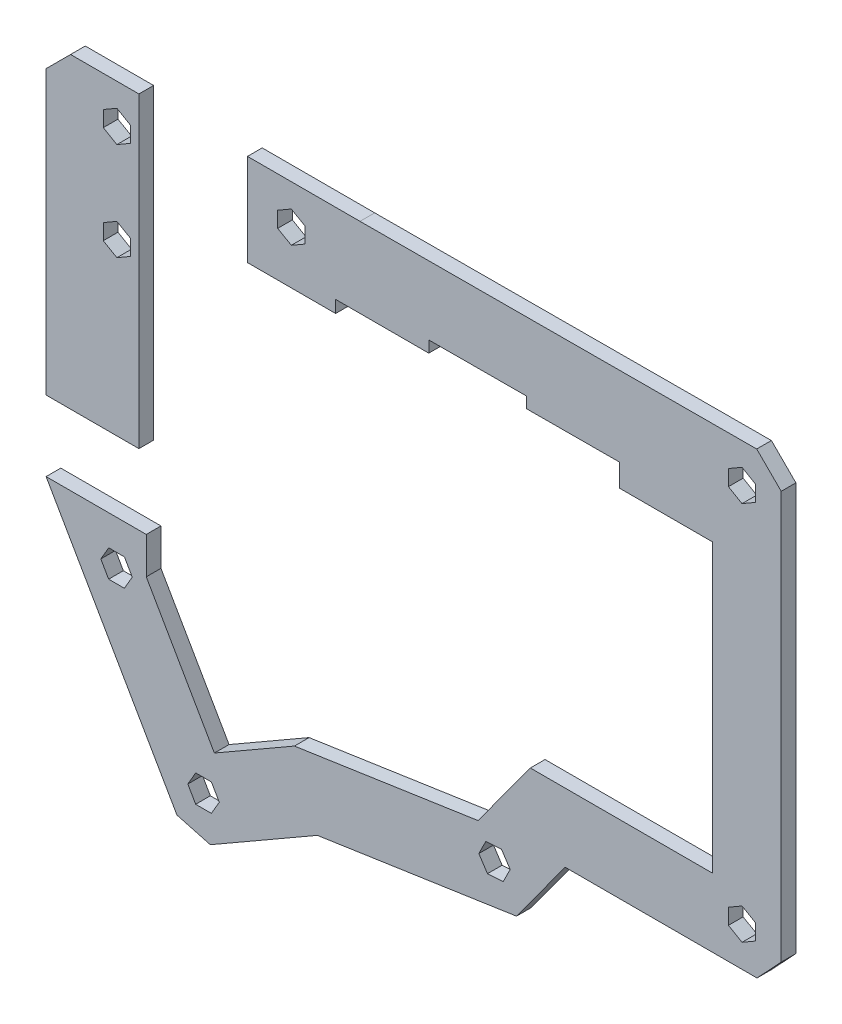
SolidWorks part; units mm, degrees
ref_plane "Plan de face" through (0, 0, 0) normal (0, 0, 1) x (1, 0, 0)
ref_plane "Plan de dessus" through (0, 0, 0) normal (0, 1, 0) x (1, 0, 0)
ref_plane "Plan de droite" through (0, 0, 0) normal (1, 0, 0) x (0, 0, -1)
sketch "Esquisse1" plane through (0, 0, 0) normal (0, 0, 1) x (1, 0, 0)
  line L0 (-117.3419, -15.4198) -> (-103.3409, -15.4198) construction
  line L1 (-103.3409, -15.4198) -> (-103.3409, -29.4208) construction
  line L2 (-103.3409, -29.4208) -> (-117.3419, -29.4208) construction
  line L3 (-117.3419, -29.4208) -> (-117.3419, -15.4198) construction
  line L4 (-98.3406, -27.0457) -> (-98.3406, -13.0447) construction
  line L5 (-98.3406, -13.0447) -> (-84.3396, -13.0447) construction
  line L6 (-84.3396, -13.0447) -> (-84.3396, -27.0457) construction
  line L7 (-84.3396, -27.0457) -> (-98.3406, -27.0457) construction
  line L8 (-79.3392, -24.6705) -> (-79.3392, -10.6695) construction
  line L9 (-79.3392, -10.6695) -> (-65.3382, -10.6695) construction
  line L10 (-65.3382, -10.6695) -> (-65.3382, -24.6705) construction
  line L11 (-65.3382, -24.6705) -> (-79.3392, -24.6705) construction
  line L12 (-60.3379, -27.0457) -> (-60.3379, -13.0447) construction
  line L13 (-60.3379, -13.0447) -> (-46.3369, -13.0447) construction
  line L14 (-46.3369, -13.0447) -> (-46.3369, -27.0457) construction
  line L15 (-46.3369, -27.0457) -> (-60.3379, -27.0457) construction
  line L16 (-41.3365, -31.796) -> (-41.3365, -17.795) construction
  line L17 (-41.3365, -17.795) -> (-27.3355, -17.795) construction
  line L18 (-27.3355, -17.795) -> (-27.3355, -31.796) construction
  line L19 (-27.3355, -31.796) -> (-41.3365, -31.796) construction
  line L20 (-22.3347, -31.796) -> (-22.3347, -17.795) construction
  line L21 (-22.3347, -17.795) -> (-8.3337, -17.795) construction
  line L22 (-8.3337, -17.795) -> (-8.3337, -31.796)
  line L23 (-8.3337, -31.796) -> (-22.3347, -31.796) construction
  line L24 (-117.3419, -34.4212) -> (-103.3409, -34.4212) construction
  line L25 (-103.3409, -34.4212) -> (-103.3409, -48.4222) construction
  line L26 (-103.3409, -48.4222) -> (-117.3419, -48.4222) construction
  line L27 (-117.3419, -48.4222) -> (-117.3419, -34.4212) construction
  line L28 (-98.3406, -32.046) -> (-84.3396, -32.046) construction
  line L29 (-84.3396, -32.046) -> (-84.3396, -46.047) construction
  line L30 (-84.3396, -46.047) -> (-98.3406, -46.047) construction
  line L31 (-98.3406, -46.047) -> (-98.3406, -32.046) construction
  line L32 (-79.3392, -29.6709) -> (-65.3382, -29.6709) construction
  line L33 (-65.3382, -29.6709) -> (-65.3382, -43.6718) construction
  line L34 (-65.3382, -43.6718) -> (-79.3392, -43.6718) construction
  line L35 (-79.3392, -43.6718) -> (-79.3392, -29.6709) construction
  line L36 (-60.3379, -32.046) -> (-46.3369, -32.046) construction
  line L37 (-46.3369, -32.046) -> (-46.3369, -46.047) construction
  line L38 (-46.3369, -46.047) -> (-60.3379, -46.047) construction
  line L39 (-60.3379, -46.047) -> (-60.3379, -32.046) construction
  line L40 (-41.3365, -36.7964) -> (-27.3355, -36.7964) construction
  line L41 (-27.3355, -36.7964) -> (-27.3355, -50.7973) construction
  line L42 (-27.3355, -50.7973) -> (-41.3365, -50.7973) construction
  line L43 (-41.3365, -50.7973) -> (-41.3365, -36.7964) construction
  line L44 (-22.3347, -36.7964) -> (-8.3337, -36.7964) construction
  line L45 (-8.3337, -36.7964) -> (-8.3337, -50.7973) construction
  line L46 (-8.3337, -50.7973) -> (-22.3347, -50.7973) construction
  line L47 (-22.3347, -50.7973) -> (-22.3347, -36.7964) construction
  line L48 (-22.3347, -55.7977) -> (-8.3337, -55.7977) construction
  line L49 (-8.3337, -55.7977) -> (-8.3337, -69.7987) construction
  line L50 (-8.3337, -69.7987) -> (-22.3347, -69.7987) construction
  line L51 (-22.3347, -69.7987) -> (-22.3347, -55.7977) construction
  line L52 (-41.3365, -55.7977) -> (-27.3355, -55.7977) construction
  line L53 (-27.3355, -55.7977) -> (-27.3355, -69.7987) construction
  line L54 (-27.3355, -69.7987) -> (-41.3365, -69.7987) construction
  line L55 (-41.3365, -69.7987) -> (-41.3365, -55.7977) construction
  line L56 (-60.3379, -51.0474) -> (-46.3369, -51.0474) construction
  line L57 (-46.3369, -51.0474) -> (-46.3369, -65.0484) construction
  line L58 (-46.3369, -65.0484) -> (-60.3379, -65.0484) construction
  line L59 (-60.3379, -65.0484) -> (-60.3379, -51.0474) construction
  line L60 (-79.3392, -48.6722) -> (-65.3382, -48.6722) construction
  line L61 (-65.3382, -48.6722) -> (-65.3382, -62.6732) construction
  line L62 (-65.3382, -62.6732) -> (-79.3392, -62.6732) construction
  line L63 (-79.3392, -62.6732) -> (-79.3392, -48.6722) construction
  line L64 (-98.3406, -51.0474) -> (-84.3396, -51.0474) construction
  line L65 (-84.3396, -51.0474) -> (-84.3396, -65.0484) construction
  line L66 (-84.3396, -65.0484) -> (-98.3406, -65.0484) construction
  line L67 (-98.3406, -65.0484) -> (-98.3406, -51.0474) construction
  line L68 (-117.3419, -53.4225) -> (-103.3409, -53.4225) construction
  line L69 (-103.3409, -53.4225) -> (-103.3409, -67.4235) construction
  line L70 (-103.3409, -67.4235) -> (-117.3419, -67.4235) construction
  line L71 (-117.3419, -67.4235) -> (-117.3419, -53.4225) construction
  line L72 (-88.8399, -70.6738) -> (-74.8389, -70.6738) construction
  line L73 (-74.8389, -70.6738) -> (-74.8389, -84.6747) construction
  line L74 (-74.8389, -84.6747) -> (-88.8399, -84.6747) construction
  line L75 (-88.8399, -84.6747) -> (-88.8399, -70.6738) construction
  line L76 (-111.4175, -75.4665) -> (-97.8899, -71.8565) construction
  line L77 (-97.8899, -71.8565) -> (-94.28, -85.3841) construction
  line L78 (-94.28, -85.3841) -> (-107.8075, -88.9941) construction
  line L79 (-107.8075, -88.9941) -> (-111.4175, -75.4665) construction
  line L80 (-134.6581, -81.5997) -> (-122.5281, -74.6075) construction
  line L81 (-122.5281, -74.6075) -> (-115.5359, -86.7375) construction
  line L82 (-115.5359, -86.7375) -> (-127.6659, -93.7297) construction
  line L83 (-127.6659, -93.7297) -> (-134.6581, -81.5997) construction
  line L86 (-25.3391, -71.9336) -> (-62.0853, -71.9336) construction
  line L89 (-72.824, -86.6446) -> (-62.0853, -71.9336) construction
  line L96 (-109.7697, -91.4639) -> (-73.0906, -86.6918) construction
  line L97 (-124.664, -99.8297) -> (-110.3971, -91.5881) construction
  line L98 (-139.9408, -76.5013) -> (-126.7151, -99.4281) construction
  line L99 (-119.8527, -15.5421) -> (-139.6028, -15.5421) construction
  line L100 (-100.8528, -13.2921) -> (-118.8527, -13.2921) construction
  line L101 (-63.8455, -8.5421) -> (-80.8528, -8.5421) construction
  line L102 (-44.8455, -10.792) -> (-62.8485, -10.792) construction
  line L103 (-25.8456, -15.5421) -> (-43.8486, -15.5421) construction
  line L104 (-6.8456, -15.5421) -> (-23.8529, -15.5421) construction
  line L105 (-6.2741, -71.3672) -> (-6.2741, -16.1136) construction
  line L106 (-23.8529, -71.9423) -> (-6.8456, -71.9423) construction
  line L107 (-61.8455, -71.9423) -> (-25.8456, -71.9423) construction
  line L108 (-72.6738, -86.4911) -> (-62.1363, -72.0583) construction
  line L109 (-140.1743, -16.1136) -> (-140.1743, -75.5958) construction
  line L110 (-134.3462, 1.5705) -> (-134.3466, -55.7217) construction
  line L111 (-134.3466, -55.7217) -> (-160.479, -70.8411) construction
  line L112 (-160.479, -70.8411) -> (-133.7613, -117.344)
  line L113 (-126.937, -119.1852) -> (-105.0783, -106.604)
  line L114 (-105.0783, -106.604) -> (-64.4097, -100.5586)
  line L115 (-64.4097, -100.5586) -> (-54.4636, -86.9336)
  line L116 (-15.2851, -86.9336) -> (-54.4636, -86.9336)
  line L117 (-10.3389, -81.6486) -> (-10.3389, 1.6248)
  line L122 (-15.3389, 6.6096) -> (-96.3687, 6.3642)
  line L129 (-10.3391, -86.9336) -> (-10.3391, -0.337) construction
  line L130 (-48.3676, 6.5096) -> (-96.3687, 6.3642) construction
  line L131 (-115.3458, 1.5705) -> (-134.3462, 1.5705) construction
  line L132 (-160.479, -3.4295) -> (-160.479, -56.4207)
  line L134 (-119.3456, 1.5429) -> (-119.3464, -12.4295)
  line L136 (-140.0228, -78.3428) -> (-140.0228, -70.8411)
  line L138 (-160.479, -70.8411) -> (-131.2704, -121.6794) construction
  line L139 (-131.2704, -121.6794) -> (-105.0783, -106.604) construction
  line L140 (-133.7613, -117.344) -> (-126.937, -119.1852)
  line L142 (-10.3389, 1.6248) -> (-15.3389, 6.6096)
  line L143 (-10.3391, -86.9336) -> (-54.4636, -86.9336) construction
  line L144 (-10.3389, -81.6486) -> (-15.2851, -86.9336)
  line L147 (-103.3652, 6.3642) -> (-96.3687, 6.3642)
  line L148 (-103.3652, 6.3642) -> (-119.3456, 6.3642)
  line L149 (-119.3456, 6.3642) -> (-119.3456, 1.5429)
  line L150 (-140.0228, 1.5705) -> (-140.0228, 6.3209) construction
  line L151 (-141.5228, 6.3209) -> (-155.479, 6.3209)
  line L152 (-160.479, 1.3209) -> (-160.479, -3.4295)
  line L153 (-155.479, 6.3209) -> (-160.479, 1.3209)
  line L154 (8.6609, -1.3177) -> (-119.3458, -1.7055) construction
  line L155 (-146.0924, -79.8227) -> (-128.3223, -110.752) construction
  line L156 (-128.3223, -110.752) -> (-107.7547, -98.9139) construction
  line L157 (-140.0228, -78.3428) -> (-126.1111, -102.5565)
  line L158 (-126.1111, -102.5565) -> (-109.762, -93.1464)
  line L159 (-109.762, -93.1464) -> (-72.2631, -87.5722)
  line L160 (-72.2631, -87.5722) -> (-61.5772, -72.9336)
  line L161 (-24.3391, -72.9336) -> (-61.5772, -72.9336)
  line L162 (-24.3391, -72.9336) -> (-24.3391, -14.337)
  line L163 (-24.3391, -14.337) -> (-43.3418, -14.337)
  line L164 (-43.3418, -14.337) -> (-43.3418, -9.7225)
  line L165 (-43.3418, -9.7225) -> (-62.3174, -9.781)
  line L166 (-62.3174, -9.781) -> (-62.3244, -7.5328)
  line L167 (-62.3244, -7.5328) -> (-82.3255, -7.5934)
  line L168 (-82.3255, -7.5934) -> (-82.3183, -9.9293)
  line L169 (-82.3183, -9.9293) -> (-101.3458, -9.9293)
  line L170 (-101.3458, -9.9293) -> (-101.3458, -12.4295)
  line L171 (-101.3458, -12.4295) -> (-119.3464, -12.4295)
  line L172 (-120.3463, -12.4295) -> (-120.3466, -63.7961) construction
  line L173 (-120.3466, -63.7961) -> (-140.5236, -75.4699) construction
  line L174 (-107.7547, -98.9139) -> (-68.8973, -93.1378) construction
  line L175 (-68.8973, -93.1378) -> (-58.5285, -78.9336) construction
  line L176 (-18.3391, -78.9336) -> (-58.5285, -78.9336) construction
  line L177 (-18.3391, -78.9336) -> (-18.3391, -1.3419) construction
  line L178 (-62.3425, -1.5328) -> (-82.3437, -1.5934) construction
  line L179 (-18.3391, -78.9336) -> (-18.3391, -14.337) construction
  line L180 (-160.479, -70.8411) -> (-140.0228, -70.8411)
  line L181 (-146.0228, -18.4678) -> (-148.8028, -20.0728)
  line L183 (-146.0228, -1.6779) -> (-146.0228, -21.6779) construction
  line L184 (-120.3463, -12.4295) -> (-120.3466, -64.3728) construction
  line L185 (-119.8474, -63.5072) -> (-140.5236, -75.4699) construction
  line L186 (-101.3458, -12.4295) -> (-120.3463, -12.4295) construction
  line L187 (-140.8899, -76.8336) -> (-126.1111, -102.5565) construction
  line L188 (-146.0228, -4.8879) -> (-143.2428, -3.2829)
  line L189 (-143.2428, -3.2829) -> (-143.2428, -0.0728)
  line L190 (-143.2428, -0.0728) -> (-146.0228, 1.5322)
  line L191 (-146.0228, 1.5322) -> (-148.8028, -0.0728)
  line L192 (-148.8028, -0.0728) -> (-148.8028, -3.2829)
  line L193 (-148.8028, -3.2829) -> (-146.0228, -4.8879)
  line L194 (-110.3971, -4.8884) -> (-107.6171, -3.2834)
  line L195 (-107.6171, -3.2834) -> (-107.6171, -0.0733)
  line L196 (-107.6171, -0.0733) -> (-110.3971, 1.5317)
  line L197 (-110.3971, 1.5317) -> (-113.1771, -0.0733)
  line L198 (-113.1771, -0.0733) -> (-113.1771, -3.2834)
  line L199 (-113.1771, -3.2834) -> (-110.3971, -4.8884)
  line L200 (-18.3391, -4.552) -> (-15.5591, -2.947)
  line L201 (-15.5591, -2.947) -> (-15.5591, 0.2631)
  line L202 (-15.5591, 0.2631) -> (-18.3391, 1.8681)
  line L203 (-18.3391, 1.8681) -> (-21.1191, 0.2631)
  line L204 (-21.1191, 0.2631) -> (-21.1191, -2.947)
  line L205 (-21.1191, -2.947) -> (-18.3391, -4.552)
  line L206 (-18.3391, -75.7236) -> (-21.1191, -77.3286)
  line L207 (-21.1191, -77.3286) -> (-21.1191, -80.5387)
  line L208 (-21.1191, -80.5387) -> (-18.3391, -82.1437)
  line L209 (-18.3391, -82.1437) -> (-15.5591, -80.5387)
  line L210 (-15.5591, -80.5387) -> (-15.5591, -77.3286)
  line L211 (-15.5591, -77.3286) -> (-18.3391, -75.7236)
  line L212 (-70.6661, -90.459) -> (-72.1016, -93.3302)
  line L213 (-72.1016, -93.3302) -> (-70.3329, -96.009)
  line L217 (-25.3391, -71.9336) -> (-25.3391, -15.337) construction
  line L220 (-25.3391, -15.337) -> (-44.3418, -15.337) construction
  line L221 (-44.3418, -15.337) -> (-44.3418, -10.7256) construction
  line L222 (-44.3418, -10.7256) -> (-63.3143, -10.7841) construction
  line L223 (-63.3143, -10.7841) -> (-63.3213, -8.5358) construction
  line L224 (-63.3213, -8.5358) -> (-81.3225, -8.5903) construction
  line L225 (-81.3225, -8.5903) -> (-81.3152, -10.9293) construction
  line L226 (-81.3152, -10.9293) -> (-100.3458, -10.9293) construction
  line L227 (-100.3458, -10.9293) -> (-100.3458, -13.4295) construction
  line L228 (-100.3458, -13.4295) -> (-119.3463, -13.4295) construction
  line L231 (-119.3463, -13.4295) -> (-119.3466, -64.3728) construction
  line L232 (-119.3466, -64.3728) -> (-140.0228, -76.3355) construction
  line L233 (-140.0228, -76.3355) -> (-125.7426, -101.1906) construction
  line L234 (-125.7426, -101.1906) -> (-110.0965, -92.1851) construction
  line L235 (-110.0965, -92.1851) -> (-72.824, -86.6446) construction
  line L236 (-70.3329, -96.009) -> (-67.1286, -95.8166)
  line L237 (-67.1286, -95.8166) -> (-65.693, -92.9454)
  line L238 (-65.693, -92.9454) -> (-67.4618, -90.2666)
  line L239 (-67.4618, -90.2666) -> (-70.6661, -90.459)
  line L240 (-129.9214, -107.9687) -> (-131.5323, -110.7453)
  line L241 (-131.5323, -110.7453) -> (-129.9331, -113.5286)
  line L242 (-129.9331, -113.5286) -> (-126.7231, -113.5354)
  line L243 (-126.7231, -113.5354) -> (-125.1122, -110.7588)
  line L244 (-125.1122, -110.7588) -> (-126.7114, -107.9754)
  line L245 (-126.7114, -107.9754) -> (-129.9214, -107.9687)
  line L246 (-144.4932, -82.606) -> (-142.8823, -79.8294)
  line L247 (-142.8823, -79.8294) -> (-144.4815, -77.0461)
  line L248 (-144.4815, -77.0461) -> (-147.6915, -77.0393)
  line L249 (-147.6915, -77.0393) -> (-149.3024, -79.8159)
  line L250 (-149.3024, -79.8159) -> (-147.7033, -82.5993)
  line L251 (-147.7033, -82.5993) -> (-144.4932, -82.606)
  line L252 (-148.8028, -20.0728) -> (-148.8028, -23.2829)
  line L253 (-148.8028, -23.2829) -> (-146.0228, -24.8879)
  line L254 (-146.0228, -24.8879) -> (-143.2428, -23.2829)
  line L255 (-143.2428, -23.2829) -> (-143.2428, -20.0728)
  line L256 (-143.2428, -20.0728) -> (-146.0228, -18.4678)
  line L257 (-140.0228, -53.4225) -> (-140.0228, -56.4207) construction
  line L259 (-140.0228, -56.4207) -> (-140.0228, 1.5705) construction
  line L260 (-141.5228, -56.4207) -> (-141.5228, 1.5705)
  line L261 (-141.5228, 1.5705) -> (-141.5228, 6.3209)
  line L262 (-141.5228, -56.4207) -> (-160.479, -56.4207)
  line L263 (-24.3391, -72.9336) -> (-24.3391, -14.337) construction
  line L328 (-48.3607, 4.2621) -> (-48.3676, 6.5096) construction
  line L329 (-29.3418, 4.3208) -> (-48.3607, 4.2621) construction
  line L330 (-29.3418, -0.337) -> (-29.3418, 4.3208) construction
  line L331 (-10.3391, -0.337) -> (-29.3418, -0.337) construction
  line L332 (-115.3458, 4.0707) -> (-115.3458, 1.5705) construction
  line L333 (-96.3616, 4.0707) -> (-115.3458, 4.0707) construction
  line L334 (-96.3687, 6.3642) -> (-96.3616, 4.0707) construction
  circle A2 centre (-18.3391, -1.3419) radius 1.6 construction
  circle A3 centre (-18.3391, -1.3419) radius 3 construction
  circle A4 centre (-110.3971, -1.6784) radius 1.6 construction
  circle A5 centre (-18.3391, -78.9336) radius 1.6 construction
  circle A6 centre (-68.8973, -93.1378) radius 1.6 construction
  circle A7 centre (-128.3223, -110.752) radius 1.6 construction
  circle A8 centre (-146.0924, -79.8227) radius 1.6 construction
  circle A9 centre (-146.0228, -1.6779) radius 1.6 construction
  circle A10 centre (-146.0228, -1.6779) radius 2.78 construction
  circle A11 centre (-110.3971, -1.6784) radius 2.78 construction
  circle A12 centre (-18.3391, -1.3419) radius 2.78 construction
  circle A13 centre (-18.3391, -78.9336) radius 2.78 construction
  circle A14 centre (-68.8973, -93.1378) radius 2.78 construction
  circle A15 centre (-128.3223, -110.752) radius 2.78 construction
  circle A16 centre (-146.0924, -79.8227) radius 2.78 construction
  circle A17 centre (-146.0228, -21.6779) radius 2.78 construction
  point P138 (-160.479, 1.5705)
  point P139 (-10.3389, 6.6248)
  point P150 (-160.479, 6.3209)
  point P197 (-15.5591, -1.3419)
  dimension "D3" = 3.2
  dimension "D4" = 6
  dimension "D6" = 3.2
  dimension "D7" = 3.2
  dimension "D8" = 3.2
  dimension "D9" = 3.2
  dimension "D10" = 3.2
  dimension "D15" = 3.2
  dimension "D2" = 6
  dimension "D1" = 15
  dimension "D16" = 5.56
  dimension "D17" = 5.56
  dimension "D18" = 5.56
  dimension "D19" = 5.56
  dimension "D20" = 5.56
  dimension "D21" = 5.56
  dimension "D22" = 5.56
  dimension "D13" = 5.56
  dimension "D5" = 1
  dimension "D23" = 1.5
extrude "Boss.-Extru.1" add sketch "Esquisse1" along normal blind 3 contours L262 L260 L261 L151 L153 L152 L132 L256 L255 L254 L253 L252 L181 L193 L192 L191 L190 L189 L188 | L180 L112 L140 L113 L114 L115 L116 L144 L117 L142 L122 L147 L148 L149 L134 L171 L170 L169 L168 L167 L166 L165 L164 L163 L162 L161 L160 L159 L158 L157 L136 L251 L250 L249 L248 L247 L246 L245 L244 L243 L242 L241 L240 L239 L238 L237 L236 L213
